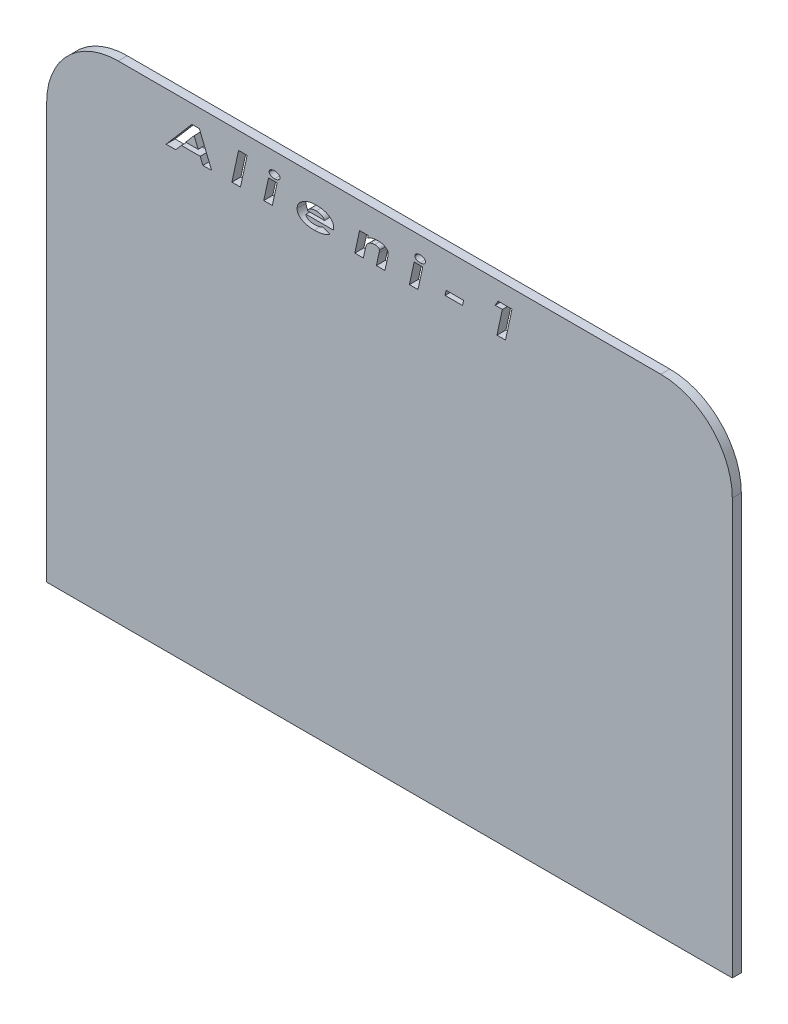
SolidWorks part; units mm, degrees
material "PLA-3d"
ref_plane "Alzado" through (0, 0, 0) normal (0, 0, 1) x (1, 0, 0)
ref_plane "Planta" through (0, 0, 0) normal (0, 1, 0) x (1, 0, 0)
ref_plane "Vista lateral" through (0, 0, 0) normal (1, 0, 0) x (0, 0, -1)
sketch "Croquis1" plane through (0, 0, 0) normal (0, 0, 1) x (1, 0, 0)
  line L0 (-57, 69) -> (-57, 3)
  line L5 (-58, 70) -> (-57, 70) construction
  line L6 (-58, 70) -> (-58, 2) construction
  line L7 (-58, 2) -> (58, 2) construction
  line L8 (58, 70) -> (58, 2) construction
  line L9 (-57, 3) -> (57, 3)
  line L10 (57, 69) -> (57, 3)
  line L12 (57, 70) -> (58, 70) construction
  line L14 (-57, 69) -> (-57, 84)
  line L15 (-57, 84) -> (57, 84)
  line L16 (57, 69) -> (57, 84)
  line L17 (-57, 69) -> (57, 69) construction
  line L18 (-58, 70) -> (58, 70) construction
  dimension "D1" = 1
  dimension "D2" = 15
extrude "Saliente-Extruir1" add sketch "Croquis1" along normal blind 1.5
sketch "Croquis2" plane through (0, 0, 1.5) normal (0, 0, 1) x (1, 0, 0)
  line L1 (-37.0135, 76) -> (51.0128, 76) construction
  line L3 (-57, 84) -> (57, 84) construction
  text T0 "<b><i>Alieni-1</i></b>" font "Century Gothic" height 5
  dimension "D1" = 8
extrude "Cortar-Extruir1" cut sketch "Croquis2" against normal up to next
sketch "Croquis3" plane through (0, 0, 1.5) normal (0, 0, 1) x (1, 0, 0)
  line L1 (-57, 70.7331) -> (-57, 72.1177)
  line L2 (-57, 84) -> (-57, 3) construction
  line L3 (-57, 84) -> (57, 84) construction
  line L4 (-45.1177, 84) -> (-40.1898, 84)
  line L5 (0, 84) -> (0, 30.8731) construction
  line L6 (-57, 84) -> (57, 84) construction
  line L7 (-57, 70.7331) -> (-71.289, 88.0986)
  line L8 (-71.289, 88.0986) -> (-41.0806, 91.4481)
  line L9 (-41.0806, 91.4481) -> (-40.1898, 84)
  line L10 (41.0806, 91.4481) -> (40.1898, 84)
  line L11 (71.289, 88.0986) -> (41.0806, 91.4481)
  line L12 (57, 70.7331) -> (71.289, 88.0986)
  line L13 (45.1177, 84) -> (40.1898, 84)
  line L14 (57, 70.7331) -> (57, 72.1177)
  arc A0 (-57, 72.1177) -> (-45.1177, 84) centre (-45.1177, 72.1177) cw
  arc A1 (57, 72.1177) -> (45.1177, 84) centre (45.1177, 72.1177) ccw
extrude "Cortar-Extruir2" cut sketch "Croquis3" against normal through all
